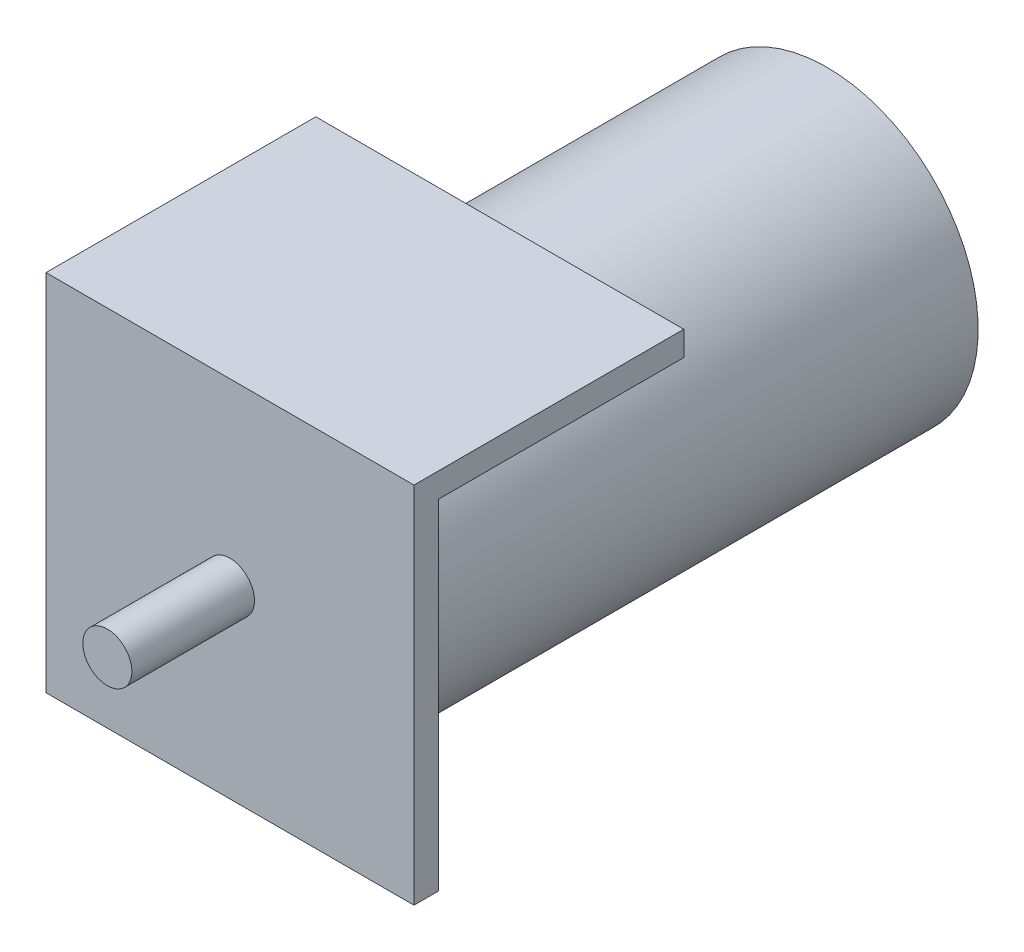
SolidWorks part; units mm, degrees
ref_plane "Front Plane" through (0, 0, 0) normal (0, 0, 1) x (1, 0, 0)
ref_plane "Top Plane" through (0, 0, 0) normal (0, 1, 0) x (1, 0, 0)
ref_plane "Right Plane" through (0, 0, 0) normal (1, 0, 0) x (0, 0, -1)
sketch "SK_Gearmotor" plane through (0, 0, 0) normal (0, 1, 0) x (1, 0, 0)
  line L0 (0, -18) -> (3, -18)
  line L1 (3, -18) -> (3, 0)
  line L2 (3, 0) -> (18.5, 0)
  line L3 (18.5, 0) -> (18.5, 70)
  line L4 (18.5, 70) -> (0, 70)
  line L5 (0, 70) -> (0, -18)
  line L6 (0, 75) -> (0, -23) construction
revolve "Gearmotor" add sketch "SK_Gearmotor" angle 360 about L6
sketch "SK_Bracket_Face" plane through (0, 0, 0) normal (1, 0, 0) x (0, 0, -1)
  line L0 (-3, -22.5) -> (0, -22.5)
  line L1 (0, -22.5) -> (0, 22)
  line L2 (0, 22) -> (-3, 22)
  line L3 (-3, 22) -> (-3, -22.5)
extrude "Bracket_Face" add sketch "SK_Bracket_Face" along normal mid plane 45
sketch "SK_Bracket_Top" plane through (0, 0, 0) normal (1, 0, 0) x (0, 0, -1)
  line L0 (-3, 19) -> (30, 19)
  line L1 (30, 19) -> (30, 22)
  line L2 (30, 22) -> (-3, 22)
  line L3 (-3, 22) -> (-3, 19)
extrude "Bracket_Top" add sketch "SK_Bracket_Top" along normal mid plane 45
